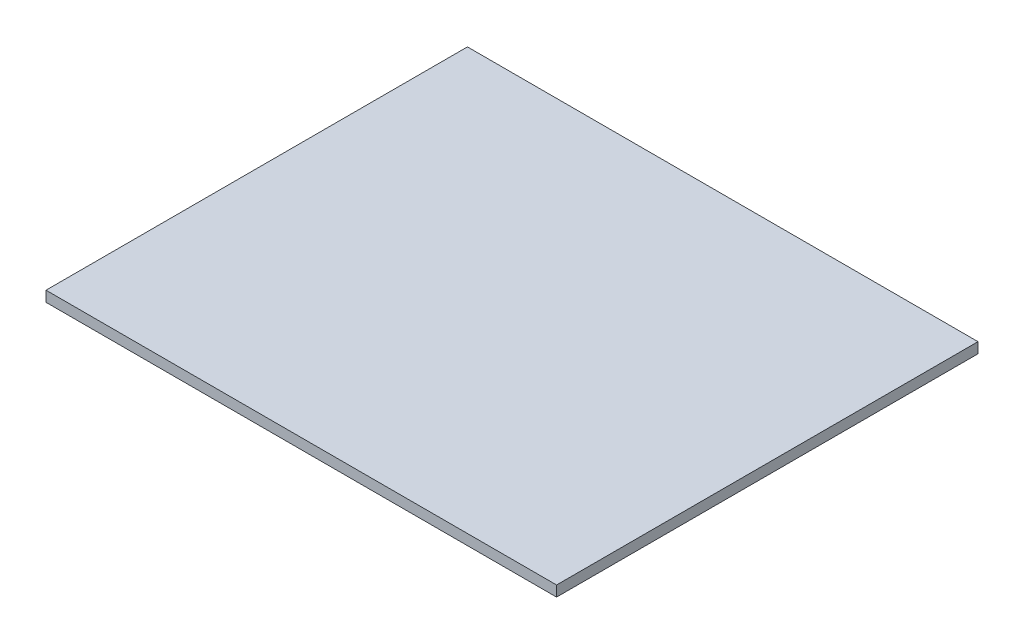
SolidWorks part; units mm, degrees
material "6061-T6 (SS)"
ref_plane "Front" through (0, 0, 0) normal (0, 0, 1) x (1, 0, 0)
ref_plane "Top" through (0, 0, 0) normal (0, 1, 0) x (1, 0, 0)
ref_plane "Right" through (0, 0, 0) normal (1, 0, 0) x (0, 0, -1)
sketch "Sketch1" plane through (0, 0, 0) normal (0, 0, 1) x (1, 0, 0)
  line L0 (-230.95, 9.525) -> (230.95, 9.525)
  line L1 (-240.475, 0) -> (240.475, 0)
  line L2 (-240.475, 0) -> (-240.475, 480.95)
  line L3 (-240.475, 480.95) -> (240.475, 480.95)
  line L4 (240.475, 0) -> (240.475, 480.95)
  line L5 (230.95, 9.525) -> (230.95, 471.425)
  line L6 (-230.95, 471.425) -> (230.95, 471.425)
  line L7 (-230.95, 9.525) -> (-230.95, 471.425)
  line L8 (-139.3649, 471.425) -> (-139.3649, 360.3167) construction
  line L9 (-230.95, 360.3167) -> (230.95, 360.3167)
  line L10 (-230.95, 360.3167) -> (-230.95, 350.7917)
  line L11 (-230.95, 350.7917) -> (230.95, 350.7917)
  line L12 (230.95, 360.3167) -> (230.95, 350.7917)
  line L13 (-230.95, 239.6833) -> (230.95, 239.6833)
  line L14 (-230.95, 239.6833) -> (-230.95, 230.1583)
  line L15 (-230.95, 230.1583) -> (230.95, 230.1583)
  line L16 (230.95, 239.6833) -> (230.95, 230.1583)
  line L17 (-230.95, 119.05) -> (230.95, 119.05)
  line L18 (-230.95, 119.05) -> (-230.95, 109.525)
  line L19 (-230.95, 109.525) -> (230.95, 109.525)
  line L20 (230.95, 119.05) -> (230.95, 109.525)
  line L21 (-139.3649, 350.7917) -> (-139.3649, 239.6833) construction
  line L22 (-139.3649, 230.1583) -> (-139.3649, 119.05) construction
  line L23 (-230.95, 415.8708) -> (-83.3333, 415.8708) construction
  line L24 (-83.3333, 471.425) -> (-73.8083, 471.425)
  line L25 (-83.3333, 471.425) -> (-83.3333, 360.3167)
  line L26 (-83.3333, 360.3167) -> (-73.8083, 360.3167)
  line L27 (-73.8083, 471.425) -> (-73.8083, 360.3167)
  line L28 (73.8083, 471.425) -> (83.3333, 471.425)
  line L29 (73.8083, 471.425) -> (73.8083, 360.3167)
  line L30 (73.8083, 360.3167) -> (83.3333, 360.3167)
  line L31 (83.3333, 471.425) -> (83.3333, 360.3167)
  line L32 (-73.8083, 415.8708) -> (73.8083, 415.8708) construction
  line L33 (83.3333, 415.8708) -> (230.95, 415.8708) construction
  dimension "D2" = 9.525
  dimension "D3" = 9.525
  dimension "D4" = 100
  dimension "D5" = 9.525
  dimension "D6" = 111.1083
  dimension "D7" = 147.6167
extrude "Boss-Extrude1" add sketch "Sketch1" along normal blind 381.25 contours L17 L20 L19 L18
